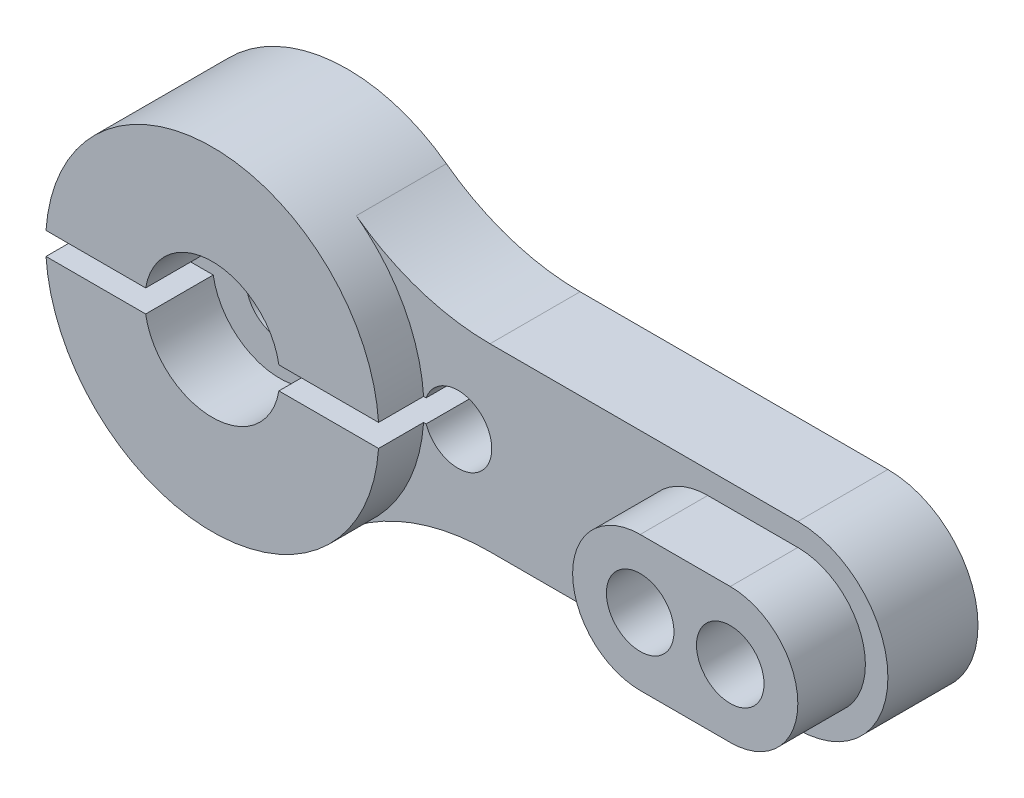
SolidWorks part; units mm, degrees
material "AISI 304"
ref_plane "正面" through (0, 0, 0) normal (0, 0, 1) x (1, 0, 0)
ref_plane "平面" through (0, 0, 0) normal (0, 1, 0) x (1, 0, 0)
ref_plane "右側面" through (0, 0, 0) normal (1, 0, 0) x (0, 0, -1)
sketch "ｽｹｯﾁ2" plane through (0, 0, 0) normal (0, 0, 1) x (1, 0, 0)
  line L0 (-7.4, 0) -> (24, 0) construction
  line L1 (24, 4) -> (10.3325, 4)
  line L2 (24, -4) -> (10.3325, -4)
  arc A0 (4.3943, 5.954) -> (4.3943, -5.954) centre (0, 0) ccw
  arc A1 (24, -4) -> (24, 4) centre (24, 0) ccw
  arc A2 (4.3943, -5.954) -> (10.3325, -4) centre (10.3325, -14) cw
  arc A3 (10.3325, 4) -> (4.3943, 5.954) centre (10.3325, 14) cw
  dimension "D1" = 14.8
  dimension "D3" = 8
  dimension "D4" = 10
  dimension "D2" = 31.4
extrude "ﾎﾞｽ - 押し出し1" add sketch "ｽｹｯﾁ2" along normal blind 4
sketch "ｽｹｯﾁ3" plane through (0, 0, 4) normal (0, 0, 1) x (1, 0, 0)
  circle A0 centre (0, 0) radius 7.4
extrude "ﾎﾞｽ - 押し出し2" add sketch "ｽｹｯﾁ3" along normal blind 2
sketch "ｽｹｯﾁ4" plane through (0, 0, 4) normal (0, 0, 1) x (1, 0, 0)
  line L0 (24, 0) -> (20, 0) construction
  line L1 (24, -3) -> (20, -3)
  line L2 (24, 3) -> (20, 3)
  arc A0 (24, -3) -> (24, 3) centre (24, 0) ccw
  arc A1 (20, 3) -> (20, -3) centre (20, 0) ccw
  point P2 (22, 0)
  dimension "D1" = 3
  dimension "D2" = 4
extrude "ﾎﾞｽ - 押し出し3" add sketch "ｽｹｯﾁ4" along normal blind 3
sketch "ｽｹｯﾁ6" plane through (0, 0, 6) normal (0, 0, 1) x (1, 0, 0)
  line L0 (-7.4, 0) -> (0, 0) construction
  line L1 (7.4, 0.5) -> (2.958, 0.5)
  line L2 (7.4, 0.5) -> (7.4, -0.5)
  line L3 (7.4, -0.5) -> (2.958, -0.5)
  line L4 (-7.4, 0.5) -> (-7.4, -0.5)
  line L5 (7.4, 0.5) -> (-7.4, -0.5) construction
  line L6 (7.4, -0.5) -> (-7.4, 0.5) construction
  line L7 (-2.958, 0.5) -> (-7.4, 0.5)
  line L8 (-2.958, -0.5) -> (-7.4, -0.5)
  arc A0 (-2.958, -0.5) -> (2.958, -0.5) centre (0, 0) ccw
  circle A1 centre (0, 0) radius 7.4 construction
  arc A2 (2.958, 0.5) -> (-2.958, 0.5) centre (0, 0) ccw
  dimension "D1" = 6
  dimension "D2" = 1
extrude "ｶｯﾄ - 押し出し1" cut sketch "ｽｹｯﾁ6" against normal blind 3
sketch "ｽｹｯﾁ7" plane through (0, 0, 7) normal (0, 0, 1) x (1, 0, 0)
  line L0 (22, 3) -> (22, -3) construction
  line L1 (24, 3) -> (20, 3) construction
  line L2 (20, -3) -> (24, -3) construction
  circle A0 centre (20, 0) radius 1.5
  circle A1 centre (24, 0) radius 1.5
  dimension "D1" = 3
extrude "ｶｯﾄ - 押し出し2" cut sketch "ｽｹｯﾁ7" against normal through all
sketch "ｽｹｯﾁ8" plane through (0, 0, 0) normal (0, 0, -1) x (-1, 0, 0)
  line L0 (0, 0) -> (-8.91, 0) construction
  line L2 (0, 0.5) -> (-8.91, 0.5)
  line L3 (0, 0.5) -> (0, -0.5)
  line L4 (0, -0.5) -> (-8.91, -0.5)
  line L5 (-8.91, 0.5) -> (-8.91, -0.5)
  line L6 (0, 0.5) -> (-8.91, -0.5) construction
  line L7 (0, -0.5) -> (-8.91, 0.5) construction
  circle A0 centre (0, 0) radius 1.5
  circle A1 centre (-8.91, 0) radius 1.5
  point P5 (-4.455, 0)
  dimension "D1" = 3
  dimension "D2" = 8.91
  dimension "D3" = 1
extrude "ｶｯﾄ - 押し出し3" cut sketch "ｽｹｯﾁ8" against normal through all contours L2 A1 L4 L5 | L4 A1 L2 L5 | L4 A0 L2 L3
sketch "ｽｹｯﾁ10" plane through (0, 0, 0) normal (0, 0, -1) x (-1, 0, 0)
  circle A0 centre (0, 0) radius 3.925
  dimension "D1" = 7.85
extrude "ｶｯﾄ - 押し出し4" cut sketch "ｽｹｯﾁ10" against normal blind 1.5
